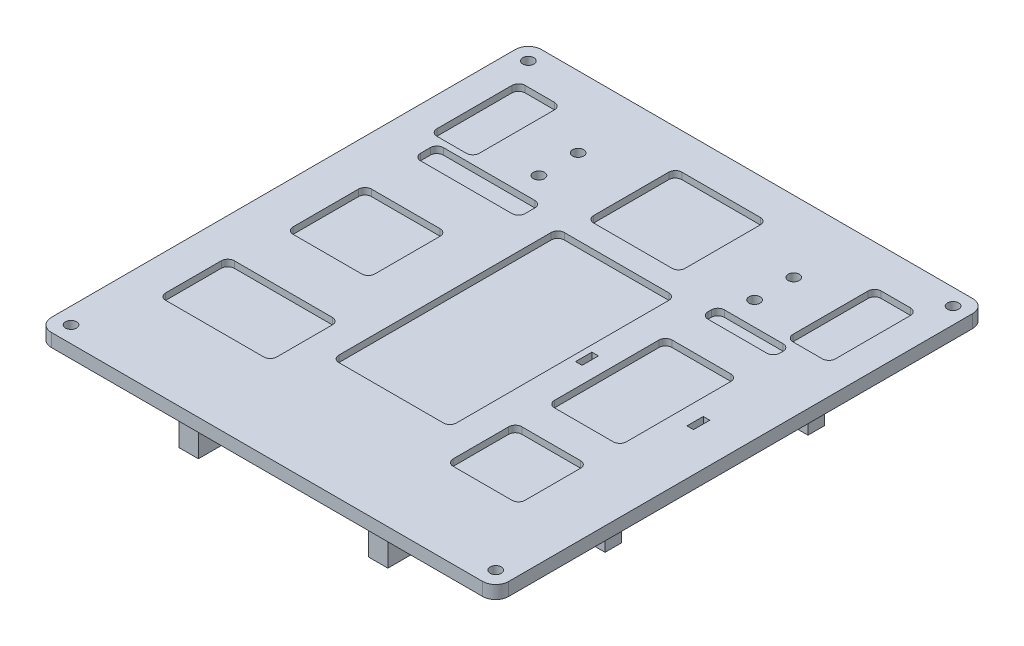
SolidWorks part; units mm, degrees
ref_plane "Front Plane" through (0, 0, 0) normal (0, 0, 1) x (1, 0, 0)
ref_plane "Top Plane" through (0, 0, 0) normal (0, 1, 0) x (1, 0, 0)
ref_plane "Right Plane" through (0, 0, 0) normal (1, 0, 0) x (0, 0, -1)
sketch "Sketch1" plane through (0, 0, 0) normal (0, 1, 0) x (1, 0, 0)
  line L1 (-66, -75) -> (66, -75)
  line L2 (-70, -71) -> (-70, 71)
  line L3 (-66, 75) -> (66, 75)
  line L4 (70, -71) -> (70, 71)
  line L5 (-70, -75) -> (70, 75) construction
  line L6 (-70, 75) -> (70, -75) construction
  arc A0 (-66, -75) -> (-70, -71) centre (-66, -71) cw
  arc A1 (66, -75) -> (70, -71) centre (66, -71) ccw
  arc A2 (66, 75) -> (70, 71) centre (66, 71) cw
  arc A3 (-70, 71) -> (-66, 75) centre (-66, 71) cw
  point P0 (0, 0)
  dimension "D1" = 4
extrude "Boss-Extrude1" add sketch "Sketch1" along normal blind 4
sketch "Sketch2" plane through (0, 4, 0) normal (0, 1, 0) x (1, 0, 0)
  line L1 (-14, -39) -> (18, -39)
  line L2 (-16, -37) -> (-16, 28)
  line L3 (-14, 30) -> (18, 30)
  line L4 (20, -37) -> (20, 28)
  line L5 (-16, -39) -> (20, 30) construction
  line L6 (-16, 30) -> (20, -39) construction
  line L7 (12, 37) -> (-12, 37)
  line L8 (14, 39) -> (14, 62)
  line L13 (12, 64) -> (-12, 64)
  line L14 (-14, 39) -> (-14, 62)
  line L19 (14, 37) -> (-14, 64) construction
  line L20 (14, 64) -> (-14, 37) construction
  line L22 (31, 29) -> (49, 29)
  line L23 (29, 31) -> (29, 32)
  line L24 (-55, -12) -> (-34, -12)
  line L25 (-57, -10) -> (-57, 10)
  line L26 (-55, 12) -> (-34, 12)
  line L27 (-32, -10) -> (-32, 10)
  line L28 (-57, -12) -> (-32, 12) construction
  line L29 (-57, 12) -> (-32, -12) construction
  line L30 (31, 34) -> (49, 34)
  line L31 (51, 31) -> (51, 32)
  line L32 (31, -18) -> (49, -18)
  line L33 (29, -16) -> (29, 16)
  line L34 (31, 18) -> (49, 18)
  line L35 (51, -16) -> (51, 16)
  line L36 (29, -18) -> (51, 18) construction
  line L37 (29, 18) -> (51, -18) construction
  line L38 (29, 29) -> (51, 34) construction
  line L39 (29, 34) -> (51, 29) construction
  line L40 (-57, -28) -> (-27, -28)
  line L41 (-59, -30) -> (-59, -47)
  line L42 (-57, -49) -> (-27, -49)
  line L43 (-25, -30) -> (-25, -47)
  line L44 (-59, -28) -> (-25, -49) construction
  line L45 (-59, -49) -> (-25, -28) construction
  line L48 (31, -49) -> (49, -49)
  line L49 (29, -47) -> (29, -30)
  line L50 (31, -28) -> (49, -28)
  line L51 (51, -47) -> (51, -30)
  line L52 (29, -49) -> (51, -28) construction
  line L53 (29, -28) -> (51, -49) construction
  line L56 (-59, 36) -> (-50, 36)
  line L57 (-61, 38) -> (-61, 61)
  line L58 (-59, 63) -> (-50, 63)
  line L59 (-48, 38) -> (-48, 61)
  line L60 (-61, 36) -> (-48, 63) construction
  line L61 (-61, 63) -> (-48, 36) construction
  line L62 (50, 36) -> (59, 36)
  line L63 (48, 38) -> (48, 61)
  line L64 (50, 63) -> (59, 63)
  line L65 (61, 38) -> (61, 61)
  line L66 (48, 36) -> (61, 63) construction
  line L67 (48, 63) -> (61, 36) construction
  line L70 (-55, 27) -> (-27, 27)
  line L71 (-57, 29) -> (-57, 32)
  line L72 (-55, 34) -> (-27, 34)
  line L73 (-25, 29) -> (-25, 32)
  line L74 (-57, 27) -> (-25, 34) construction
  line L75 (-57, 34) -> (-25, 27) construction
  arc A0 (-16, 28) -> (-14, 30) centre (-14, 28) cw
  arc A1 (-14, -39) -> (-16, -37) centre (-14, -37) cw
  arc A2 (18, -39) -> (20, -37) centre (18, -37) ccw
  arc A3 (18, 30) -> (20, 28) centre (18, 28) cw
  arc A4 (-12, 37) -> (-14, 39) centre (-12, 39) cw
  arc A5 (12, 37) -> (14, 39) centre (12, 39) ccw
  arc A6 (14, 62) -> (12, 64) centre (12, 62) ccw
  arc A7 (-12, 64) -> (-14, 62) centre (-12, 62) ccw
  arc A8 (-57, 10) -> (-55, 12) centre (-55, 10) cw
  arc A9 (-55, -12) -> (-57, -10) centre (-55, -10) cw
  arc A10 (-34, -12) -> (-32, -10) centre (-34, -10) ccw
  arc A11 (-34, 12) -> (-32, 10) centre (-34, 10) cw
  arc A12 (49, -18) -> (51, -16) centre (49, -16) ccw
  arc A13 (31, -18) -> (29, -16) centre (31, -16) cw
  arc A14 (29, 16) -> (31, 18) centre (31, 16) cw
  arc A15 (49, 18) -> (51, 16) centre (49, 16) cw
  arc A16 (-59, -47) -> (-57, -49) centre (-57, -47) ccw
  arc A17 (-27, -49) -> (-25, -47) centre (-27, -47) ccw
  arc A18 (-27, -28) -> (-25, -30) centre (-27, -30) cw
  arc A19 (-57, -28) -> (-59, -30) centre (-57, -30) ccw
  arc A20 (49, -49) -> (51, -47) centre (49, -47) ccw
  arc A21 (31, -49) -> (29, -47) centre (31, -47) cw
  arc A22 (49, -28) -> (51, -30) centre (49, -30) cw
  arc A23 (29, -30) -> (31, -28) centre (31, -30) cw
  arc A24 (-50, 36) -> (-48, 38) centre (-50, 38) ccw
  arc A25 (-59, 36) -> (-61, 38) centre (-59, 38) cw
  arc A26 (-50, 63) -> (-48, 61) centre (-50, 61) cw
  arc A27 (-61, 61) -> (-59, 63) centre (-59, 61) cw
  arc A28 (59, 36) -> (61, 38) centre (59, 38) ccw
  arc A29 (50, 36) -> (48, 38) centre (50, 38) cw
  arc A30 (59, 63) -> (61, 61) centre (59, 61) cw
  arc A31 (48, 61) -> (50, 63) centre (50, 61) cw
  arc A32 (-27, 34) -> (-25, 32) centre (-27, 32) cw
  arc A33 (-27, 27) -> (-25, 29) centre (-27, 29) ccw
  arc A34 (-55, 27) -> (-57, 29) centre (-55, 29) cw
  arc A35 (-57, 32) -> (-55, 34) centre (-55, 32) cw
  arc A36 (49, 29) -> (51, 31) centre (49, 31) ccw
  arc A37 (49, 34) -> (51, 32) centre (49, 32) cw
  arc A38 (31, 29) -> (29, 31) centre (31, 31) cw
  arc A39 (29, 32) -> (31, 34) centre (31, 32) cw
  point P0 (2, -4.5)
  point P17 (0, 50.5)
  point P21 (-42, -38.5)
  point P23 (-44.5, 0)
  point P40 (40, 0)
  point P73 (40, -38.5)
  point P90 (54.5, 49.5)
  point P106 (-54.5, 49.5)
  point P124 (-41, 30.5)
  point P141 (40, 31.5)
  dimension "D5" = 2
  dimension "D6" = 2
  dimension "D7" = 2
  dimension "D8" = 2
  dimension "D9" = 2
  dimension "D14" = 2
  dimension "D13" = 2
  dimension "D15" = 2
  dimension "D3" = 22
  dimension "D4" = 21
extrude "Cut-Extrude2" cut sketch "Sketch2" against normal blind 2
sketch "Sketch3" plane through (0, 0, 0) normal (0, -1, 0) x (1, 0, 0)
  line L0 (70, 0) -> (-96.4755, 0) construction
  line L1 (70, 71) -> (70, -71) construction
  line L2 (-66, 75) -> (66, 75) construction
  line L3 (40, -75) -> (40, 85.1735) construction
  line L4 (66, -75) -> (-66, -75) construction
  line L5 (62.05, -28.55) -> (57.05, -33.55) construction
  line L6 (20.95, -2.5) -> (22.95, -2.5)
  line L7 (20.95, -2.5) -> (20.95, 2.5)
  line L8 (20.95, 2.5) -> (22.95, 2.5)
  line L9 (22.95, -2.5) -> (22.95, 2.5)
  line L10 (20.95, -2.5) -> (22.95, 2.5) construction
  line L11 (20.95, 2.5) -> (22.95, -2.5) construction
  line L16 (62.05, -33.55) -> (57.05, -28.55) construction
  line L17 (62.05, 33.55) -> (57.05, 28.55) construction
  line L18 (17.95, 28.55) -> (22.95, 28.55)
  line L19 (17.95, 28.55) -> (17.95, 33.55)
  line L20 (17.95, 33.55) -> (22.95, 33.55)
  line L21 (22.95, 28.55) -> (22.95, 33.55)
  line L22 (17.95, 28.55) -> (22.95, 33.55) construction
  line L23 (17.95, 33.55) -> (22.95, 28.55) construction
  line L28 (62.05, 28.55) -> (57.05, 33.55) construction
  line L29 (59.05, 2.5) -> (57.05, -2.5) construction
  line L34 (17.95, -33.55) -> (22.95, -33.55)
  line L35 (17.95, -33.55) -> (17.95, -28.55)
  line L40 (17.95, -28.55) -> (22.95, -28.55)
  line L41 (22.95, -33.55) -> (22.95, -28.55)
  line L42 (17.95, -33.55) -> (22.95, -28.55) construction
  line L43 (17.95, -28.55) -> (22.95, -33.55) construction
  line L44 (59.05, -2.5) -> (57.05, 2.5) construction
  line L45 (57.05, -33.55) -> (57.05, -28.55)
  line L46 (62.05, -28.55) -> (57.05, -28.55)
  line L47 (62.05, -33.55) -> (62.05, -28.55)
  line L48 (62.05, -33.55) -> (57.05, -33.55)
  line L49 (57.05, 28.55) -> (57.05, 33.55)
  line L50 (62.05, 33.55) -> (57.05, 33.55)
  line L51 (62.05, 28.55) -> (62.05, 33.55)
  line L52 (62.05, 28.55) -> (57.05, 28.55)
  line L53 (57.05, -2.5) -> (57.05, 2.5)
  line L54 (59.05, 2.5) -> (57.05, 2.5)
  line L55 (59.05, -2.5) -> (59.05, 2.5)
  line L56 (59.05, -2.5) -> (57.05, -2.5)
  line L57 (46.5, 23) -> (49.5, 25) construction
  line L62 (46.5, 25) -> (49.5, 23) construction
  line L63 (49.5, 25) -> (49.5, 23)
  line L68 (46.5, 23) -> (49.5, 23)
  line L69 (46.5, 25) -> (46.5, 23)
  line L70 (30.5, -25) -> (33.5, -25)
  line L71 (30.5, -25) -> (30.5, -23)
  line L72 (30.5, -23) -> (33.5, -23)
  line L73 (33.5, -25) -> (33.5, -23)
  line L74 (30.5, -25) -> (33.5, -23) construction
  line L75 (30.5, -23) -> (33.5, -25) construction
  line L76 (46.5, -25) -> (49.5, -25)
  line L77 (46.5, -25) -> (46.5, -23)
  line L78 (46.5, -23) -> (49.5, -23)
  line L79 (49.5, -25) -> (49.5, -23)
  line L80 (46.5, -25) -> (49.5, -23) construction
  line L81 (46.5, -23) -> (49.5, -25) construction
  line L82 (46.5, 25) -> (49.5, 25)
  line L83 (30.5, 23) -> (33.5, 25) construction
  line L84 (30.5, 25) -> (33.5, 23) construction
  line L85 (33.5, 25) -> (33.5, 23)
  line L86 (30.5, 23) -> (33.5, 23)
  line L87 (30.5, 25) -> (30.5, 23)
  line L88 (30.5, 25) -> (33.5, 25)
  point P11 (21.95, 0)
  point P21 (20.45, 31.05)
  point P31 (20.45, -31.05)
  point P38 (59.55, -31.05)
  point P39 (59.55, 31.05)
  point P40 (58.05, 0)
  point P45 (48, 24)
  point P50 (32, 24)
  point P51 (32, -24)
  point P56 (48, -24)
  point P61 (0, 0)
  dimension "D1" = 75
  dimension "D2" = 30
  dimension "D3" = 5
  dimension "D4" = 2
  dimension "D5" = 28.55
  dimension "D6" = 17.05
  dimension "D7" = 5
  dimension "D8" = 5
  dimension "D9" = 17.05
  dimension "D10" = 17.05
  dimension "D11" = 5
  dimension "D12" = 5
  dimension "D13" = 17.05
  dimension "D15" = 28.55
  dimension "D16" = 8
  dimension "D17" = 8
  dimension "D18" = 24
  dimension "D19" = 24
extrude "Boss-Extrude4" add sketch "Sketch3" along normal blind 11 contours L19 L18 L21 L20 | L49 L50 L51 L52 | L35 L34 L41 L40 | L45 L46 L47 L48
sketch "Sketch5" plane through (0, 0, 0) normal (0, -1, 0) x (1, 0, 0)
  line L0 (40, 75) -> (40, -76.6765)
  line L1 (-66, 75) -> (66, 75) construction
  line L2 (83.6961, 0) -> (-87.296, 0)
  line L3 (70, 71) -> (70, -71) construction
  line L4 (33.5, 23) -> (30.5, 25) construction
  line L9 (33.5, 25) -> (30.5, 23) construction
  line L10 (30.5, 25) -> (30.5, 23)
  line L11 (46.5, 25) -> (49.5, 25)
  line L12 (46.5, 25) -> (46.5, 23)
  line L13 (46.5, 23) -> (49.5, 23)
  line L14 (49.5, 25) -> (49.5, 23)
  line L15 (46.5, 25) -> (49.5, 23) construction
  line L16 (46.5, 23) -> (49.5, 25) construction
  line L17 (33.5, 23) -> (30.5, 23)
  line L18 (33.5, 25) -> (33.5, 23)
  line L19 (33.5, 25) -> (30.5, 25)
  line L20 (46.5, -23) -> (49.5, -25) construction
  line L21 (46.5, -25) -> (49.5, -23) construction
  line L22 (49.5, -25) -> (49.5, -23)
  line L23 (46.5, -23) -> (49.5, -23)
  line L24 (46.5, -25) -> (46.5, -23)
  line L25 (46.5, -25) -> (49.5, -25)
  line L26 (33.5, -25) -> (30.5, -23) construction
  line L27 (33.5, -23) -> (30.5, -25) construction
  line L28 (33.5, -25) -> (30.5, -25)
  line L29 (33.5, -25) -> (33.5, -23)
  line L30 (33.5, -23) -> (30.5, -23)
  line L31 (30.5, -25) -> (30.5, -23)
  point P10 (48, 24)
  point P13 (32, 24)
  point P22 (48, -24)
  point P27 (32, -24)
  dimension "D1" = 75
  dimension "D2" = 30
  dimension "D3" = 8
  dimension "D4" = 24
  dimension "D5" = 3
  dimension "D6" = 2
extrude "Boss-Extrude5" add sketch "Sketch5" along normal blind 8 contours L10 L17 L18 L19 | L12 L11 L14 L13 | L28 L31 L30 L29 | L22 L23 L24 L25
sketch "Sketch6" plane through (0, 0, 0) normal (0, -1, 0) x (1, 0, 0)
  line L0 (70, 0) -> (-14.3024, 0)
  line L1 (70, 71) -> (70, -71) construction
  line L2 (40, 77.4829) -> (40, -75)
  line L3 (66, -75) -> (-66, -75) construction
  line L5 (21.95, -2.5) -> (23.95, -2.5)
  line L6 (21.95, -2.5) -> (21.95, 2.5)
  line L7 (21.95, 2.5) -> (23.95, 2.5)
  line L8 (23.95, -2.5) -> (23.95, 2.5)
  line L9 (21.95, -2.5) -> (23.95, 2.5) construction
  line L10 (21.95, 2.5) -> (23.95, -2.5) construction
  line L11 (56.05, -2.5) -> (58.05, -2.5)
  line L12 (56.05, -2.5) -> (56.05, 2.5)
  line L13 (56.05, 2.5) -> (58.05, 2.5)
  line L14 (58.05, -2.5) -> (58.05, 2.5)
  line L15 (56.05, -2.5) -> (58.05, 2.5) construction
  line L16 (56.05, 2.5) -> (58.05, -2.5) construction
  point P9 (22.95, 0)
  point P14 (57.05, 0)
  point P19 (0, 0)
  point P20 (40, 1.2414)
  dimension "D1" = 30
  dimension "D2" = 2
  dimension "D3" = 5
  dimension "D4" = 2
  dimension "D5" = 5
  dimension "D6" = 17.05
  dimension "D7" = 17.05
extrude "Cut-Extrude3" cut sketch "Sketch6" against normal blind 4 contours L5 L8 L0 L6 | L0 L8 L7 L6 | L0 L14 L13 L12 | L11 L14 L0 L12
sketch "Sketch7" plane through (0, 0, 0) normal (0, -1, 0) x (1, 0, 0)
  line L0 (0, 78.8364) -> (0, -82.7962)
  line L1 (-108.6372, 0) -> (96.1934, 0)
  line L4 (-70, -71) -> (-70, 71) construction
  line L5 (66, -75) -> (-66, -75) construction
  circle A0 centre (-65, 70) radius 1.7
  circle A1 centre (65, 70) radius 1.7
  circle A2 centre (65, -70) radius 1.7
  circle A3 centre (-65, -70) radius 1.7
  circle A4 centre (-33, -53.2279) radius 1.7
  circle A5 centre (-33, -41.2279) radius 1.7
  circle A6 centre (33, -41.2279) radius 1.7
  circle A7 centre (33, -53.2279) radius 1.7
  circle A8 centre (-63.75, 18.75) radius 3.5
  circle A10 centre (-63.75, -18.75) radius 3.5
  circle A11 centre (-26.25, -18.75) radius 3.5
  circle A12 centre (-26.25, 18.75) radius 3.5
  circle A13 centre (-63.75, 18.75) radius 1.25
  circle A14 centre (-26.25, 18.75) radius 1.25
  circle A15 centre (-63.75, -18.75) radius 1.25
  circle A16 centre (-26.25, -18.75) radius 1.25
  point P37 (0, 0)
  dimension "D1" = 6.25
  dimension "D4" = 56.25
  dimension "D8" = 37.5
  dimension "D3" = 7
  dimension "D2" = 37.5
  dimension "D5" = 6.25
  dimension "D6" = 37.5
  dimension "D7" = 33
  dimension "D9" = 37.5
  dimension "D10" = 37.5
extrude "Boss-Extrude6" add sketch "Sketch7" along normal blind 6 contours A8 | A13 | A12 | A14 | A10 | A15 | A16 | A11
sketch "Sketch8" plane through (0, 0, 0) normal (0, -1, 0) x (1, 0, 0)
  line L0 (0.015, 78.8373) -> (0.015, -82.7952)
  line L1 (-108.6221, 0.0009) -> (96.2084, 0.0009)
  circle A0 centre (-64.985, 70.0009) radius 1.7
  circle A1 centre (65.015, 70.0009) radius 1.7
  circle A2 centre (65.015, -69.9991) radius 1.7
  circle A3 centre (-64.985, -69.9991) radius 1.7
  circle A4 centre (-32.985, -53.227) radius 1.7
  circle A5 centre (-32.985, -41.227) radius 1.7
  circle A6 centre (33.015, -41.227) radius 1.7
  circle A7 centre (33.015, -53.227) radius 1.7
  circle A8 centre (-63.735, 18.7509) radius 3.5
  circle A9 centre (-63.735, -18.7491) radius 3.5
  circle A10 centre (-26.235, -18.7491) radius 3.5
  circle A11 centre (-26.235, 18.7509) radius 3.5
  circle A12 centre (-63.735, 18.7509) radius 1.25
  circle A13 centre (-26.235, 18.7509) radius 1.25
  circle A14 centre (-63.735, -18.7491) radius 1.25
  circle A15 centre (-26.235, -18.7491) radius 1.25
  point P32 (0, 0)
  dimension "D2" = 7
  dimension "D1" = 33
  dimension "D3" = 37.5
  dimension "D4" = 37.5
  dimension "D5" = 37.5
  dimension "D6" = 37.5
  dimension "D7" = 37.5
extrude "Cut-Extrude4" cut sketch "Sketch8" against normal blind 4 contours A0 | A1 | A3 | A4 | A5 | A7 | A6 | A2
sketch "Sketch9" plane through (0, 0, 0) normal (0, -1, 0) x (1, 0, 0)
  line L0 (0, 78.8364) -> (0, -82.7962) construction
  line L1 (-32, 55) -> (-26, 55)
  line L2 (-32, 55) -> (-32, 70)
  line L3 (-32, 70) -> (-26, 70)
  line L4 (-26, 55) -> (-26, 70)
  line L5 (-32, 55) -> (-26, 70) construction
  line L6 (-32, 70) -> (-26, 55) construction
  line L7 (-66, 75) -> (66, 75) construction
  line L8 (0, 96.8286) -> (0, -7.9067) construction
  line L21 (-19, 42) -> (19, 42)
  line L22 (-19, 42) -> (-19, 48)
  line L23 (-19, 48) -> (19, 48)
  line L24 (19, 42) -> (19, 48)
  line L25 (-19, 42) -> (19, 48) construction
  line L26 (-19, 48) -> (19, 42) construction
  line L27 (32, 70) -> (26, 55) construction
  line L28 (32, 55) -> (26, 70) construction
  line L29 (26, 55) -> (26, 70)
  line L30 (32, 70) -> (26, 70)
  line L31 (32, 55) -> (32, 70)
  line L32 (32, 55) -> (26, 55)
  circle A0 centre (-29, 62.5) radius 1
  circle A1 centre (29, 62.5) radius 1
  point P0 (-29, 62.5)
  point P19 (0, 45)
  point P31 (29, 62.5)
  dimension "D1" = 26
  dimension "D2" = 5
  dimension "D3" = 6
  dimension "D4" = 38
  dimension "D5" = 30
extrude "Boss-Extrude7" add sketch "Sketch9" along normal blind 12 contours L2 L1 L4 L3 | L29 L30 L31 L32 | A1 | A0
sketch "Sketch10" plane through (0, 0, 0) normal (0, -1, 0) x (1, 0, 0)
  line L0 (0, 78.8364) -> (0, -82.7962) construction
  line L7 (-66, 75) -> (66, 75) construction
  line L12 (-19, 42) -> (19, 42)
  line L13 (-19, 42) -> (-19, 48)
  line L14 (-19, 48) -> (19, 48)
  line L15 (19, 42) -> (19, 48)
  line L16 (-19, 42) -> (19, 48) construction
  line L17 (-19, 48) -> (19, 42) construction
  point P7 (0, 45)
  dimension "D1" = 38
  dimension "D2" = 6
  dimension "D3" = 30
extrude "Boss-Extrude9" add sketch "Sketch10" along normal blind 6
sketch "Sketch11" plane through (0, 0, 42) normal (0, 0, -1) x (-1, 0, 0)
  line L0 (108.6372, 0) -> (-96.1934, 0) construction
  line L1 (19, -6) -> (19, 0) construction
  circle A0 centre (15, -3) radius 1
  circle A1 centre (-15, -3) radius 1
  dimension "D1" = 3
  dimension "D2" = 3
  dimension "D3" = 30
  dimension "D4" = 4
extrude "Cut-Extrude5" cut sketch "Sketch11" against normal blind 6
